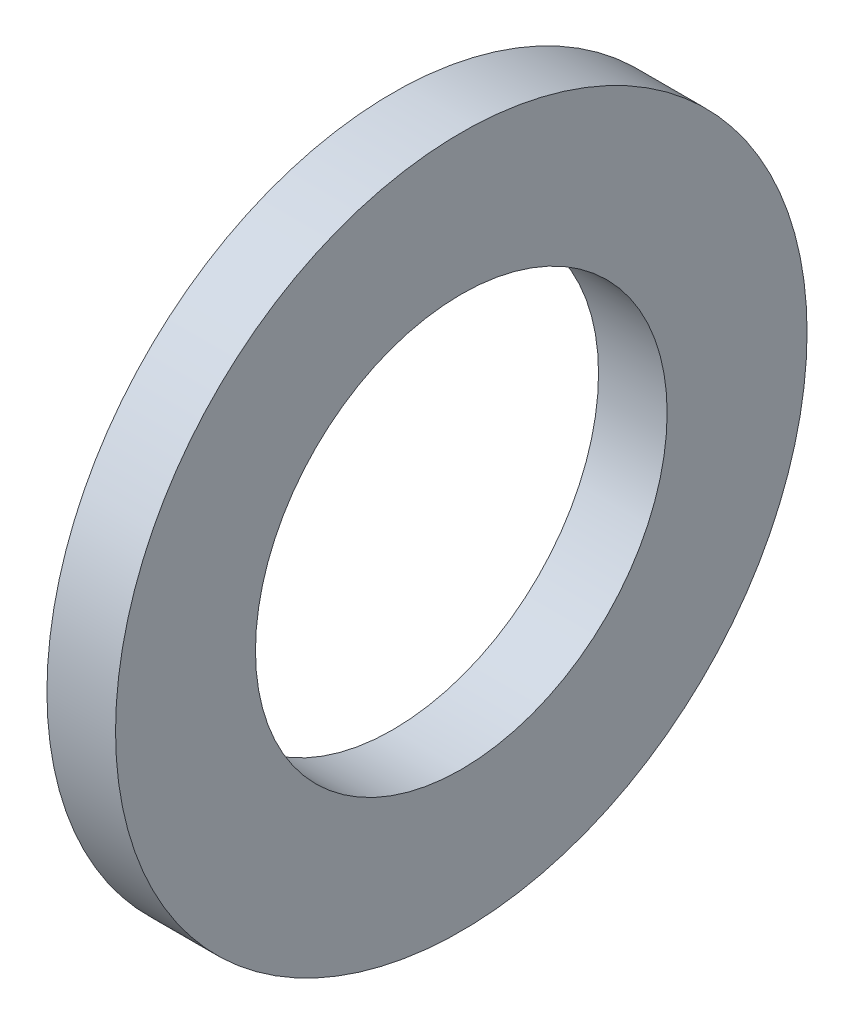
SolidWorks part; units mm, degrees
material "POM Acetal Copolymer"
ref_plane "Front Plane" through (0, 0, 0) normal (0, 0, 1) x (1, 0, 0)
ref_plane "Top Plane" through (0, 0, 0) normal (0, 1, 0) x (1, 0, 0)
ref_plane "Right Plane" through (0, 0, 0) normal (1, 0, 0) x (0, 0, -1)
sketch "Sketch1" plane through (0, 0, 0) normal (1, 0, 0) x (0, 0, -1)
  circle A0 centre (0, 0) radius 2.3813
  circle A1 centre (0, 0) radius 4
  dimension "D1" = 4.7625
  dimension "D2" = 8
extrude "Boss-Extrude1" add sketch "Sketch1" along normal blind 0.7937
